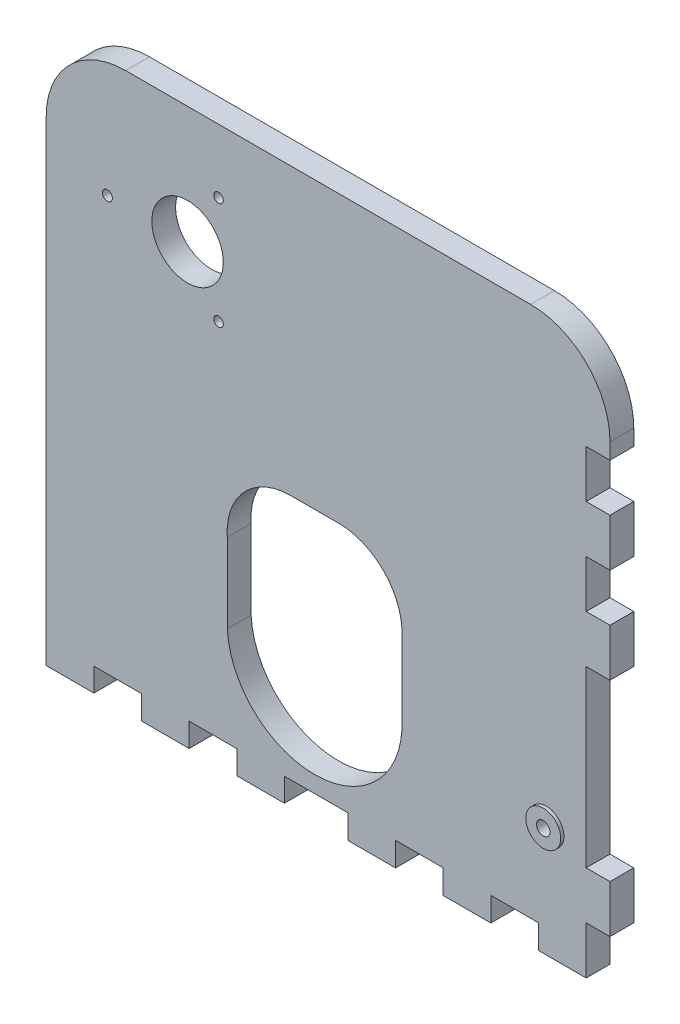
SolidWorks part; units mm, degrees
ref_plane "Front Plane" through (0, 0, 0) normal (0, 0, 1) x (1, 0, 0)
ref_plane "Top Plane" through (0, 0, 0) normal (0, 1, 0) x (1, 0, 0)
ref_plane "Right Plane" through (0, 0, 0) normal (1, 0, 0) x (0, 0, -1)
sketch "Sketch1" plane through (0, 0, 0) normal (0, 0, 1) x (1, 0, 0)
  line L0 (-120, 172.7057) -> (135, 172.7057)
  line L1 (140, -177.1701) -> (170, -177.1701)
  line L2 (-170, -167.2943) -> (-170, 122.7057)
  line L3 (-127.5, 103.8145) -> (-127.5, 87.929) construction
  line L4 (-55.9954, -49.8) -> (-55.9954, -99.8)
  line L5 (54.0046, -99.8) -> (54.0046, -49.8)
  line L6 (14.7319, -7.1009) -> (-16.7227, -7.1009)
  line L7 (-117.8586, 98.85) -> (-151.8742, 98.85) construction
  line L9 (170, -177.1701) -> (170, -162.0943)
  line L10 (-170, -167.2943) -> (-170, -176.8016)
  line L11 (-170, -176.8016) -> (-140, -176.8016)
  line L12 (-140, -176.8016) -> (-140, -162.0943)
  line L13 (-140, -162.0943) -> (-110, -162.0943)
  line L14 (-110, -162.0943) -> (-110, -177.0342)
  line L15 (-110, -177.0342) -> (-80, -177.0342)
  line L16 (-80, -177.0342) -> (-80, -162.0943)
  line L17 (-80, -162.0943) -> (-50, -162.0943)
  line L18 (-50, -162.0943) -> (-50, -176.8656)
  line L19 (-50, -176.8656) -> (-20, -176.8656)
  line L20 (-20, -176.8656) -> (-20, -162.0943)
  line L21 (-20, -162.0943) -> (20, -162.0943)
  line L22 (20, -162.0943) -> (20, -177.1651)
  line L23 (20, -177.1651) -> (50, -177.1651)
  line L24 (50, -177.1651) -> (50, -162.0943)
  line L25 (50, -162.0943) -> (80, -162.0943)
  line L26 (80, -162.0943) -> (80, -177.1822)
  line L27 (80, -177.1822) -> (110, -177.1822)
  line L28 (110, -177.1822) -> (110, -162.0943)
  line L29 (110, -162.0943) -> (140, -162.0943)
  line L30 (140, -162.0943) -> (140, -177.1701)
  line L34 (170, -162.0943) -> (170, -147.0943)
  line L35 (170, -147.0943) -> (185, -147.0943)
  line L36 (185, -147.0943) -> (185, -117.0943)
  line L37 (185, -117.0943) -> (170, -117.0943)
  line L38 (170, -117.0943) -> (170, -7.2943)
  line L39 (170, -7.2943) -> (185, -7.2943)
  line L40 (185, -7.2943) -> (185, 22.7057)
  line L41 (185, 22.7057) -> (170, 22.7057)
  line L42 (170, 22.7057) -> (170, 52.7057)
  line L43 (170, 52.7057) -> (185, 52.7057)
  line L44 (185, 52.7057) -> (185, 82.7057)
  line L45 (185, 82.7057) -> (170, 82.7057)
  line L46 (170, 82.7057) -> (170, 112.7057)
  line L47 (7.5, 172.7057) -> (7.5, 82.7057) construction
  line L51 (185, 122.7057) -> (185, 112.7057)
  line L52 (185, 112.7057) -> (170, 112.7057)
  circle A0 centre (145, -107) radius 11
  arc A1 (-16.7227, -7.1009) -> (-55.9954, -49.8) centre (-16.0869, -47.0959) ccw
  arc A2 (-55.9954, -99.8) -> (54.0046, -99.8) centre (-0.9954, -96.6294) ccw
  arc A3 (54.0046, -49.8) -> (14.7319, -7.1009) centre (14.0961, -47.0959) ccw
  arc A4 (-170, 122.7057) -> (-120, 172.7057) centre (-120, 122.7057) cw
  circle A5 centre (-131.5, 98.85) radius 3.1426
  circle A6 centre (-81, 98.85) radius 22.5
  circle A7 centre (-61.5, 65.075) radius 3
  circle A8 centre (-61.5, 132.625) radius 3
  arc A9 (54.0046, -47.0943) -> (14.0046, -7.0943) centre (14.0046, -47.0943) ccw construction
  arc A10 (-15.9954, -7.0943) -> (-55.9954, -47.0943) centre (-15.9954, -47.0943) ccw construction
  arc A11 (185, 122.7057) -> (135, 172.7057) centre (135, 122.7057) ccw
  point P0 (0, 0)
  point P75 (-127.5, 98.85)
  dimension "D5" = 22
  dimension "D28" = 50
  dimension "D3" = 50
  dimension "D7" = 30
  dimension "D8" = 30
  dimension "D9" = 30
  dimension "D10" = 30
  dimension "D11" = 30
  dimension "D12" = 40
  dimension "D13" = 30
  dimension "D14" = 30
  dimension "D15" = 30
  dimension "D16" = 30
extrude "Boss-Extrude1" add sketch "Sketch1" along normal blind 15
ref_plane "Plane1" through (0, 0, 17) normal (0, 0, -1) x (-1, 0, 0)
sketch "Sketch3" plane through (0, 0, 17) normal (0, 0, -1) x (-1, 0, 0)
  circle A0 centre (-145, -107) radius 11
  circle A1 centre (-145, -107) radius 4.25
  dimension "D1" = 8.5
extrude "Boss-Extrude2" add sketch "Sketch3" along normal blind 10
